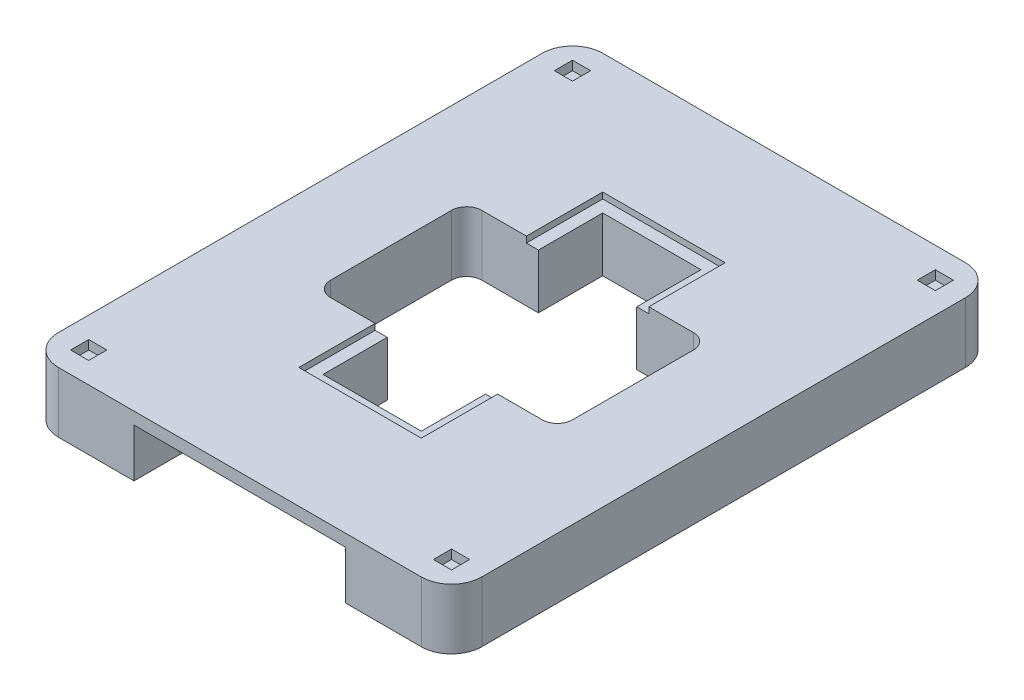
SolidWorks part; units mm, degrees
ref_plane "前视基准面" through (0, 0, 0) normal (0, 0, 1) x (1, 0, 0)
ref_plane "上视基准面" through (0, 0, 0) normal (0, 1, 0) x (1, 0, 0)
ref_plane "右视基准面" through (0, 0, 0) normal (1, 0, 0) x (0, 0, -1)
sketch "草图1" plane through (0, 0, 0) normal (0, 1, 0) x (1, 0, 0)
  line L1 (100, -100) -> (-100, -100)
  line L2 (100, -100) -> (100, 100)
  line L3 (100, 100) -> (-100, 100)
  line L4 (-100, -100) -> (-100, 100)
  line L5 (100, -100) -> (-100, 100) construction
  line L6 (100, 100) -> (-100, -100) construction
  point P1 (0, 0)
  dimension "D1" = 200
  dimension "D2" = 200
extrude "凸台-拉伸1" add sketch "草图1" along normal blind 20
sketch "草图2" plane through (0, 20, 0) normal (0, 1, 0) x (1, 0, 0)
  line L1 (70, -90) -> (-70, -90)
  line L2 (70, -90) -> (70, 90)
  line L3 (70, 90) -> (-70, 90)
  line L4 (-70, -90) -> (-70, 90)
  line L5 (70, -90) -> (-70, 90) construction
  line L6 (70, 90) -> (-70, -90) construction
  line L7 (100, -100) -> (-100, -100)
  line L8 (100, -100) -> (100, 100)
  line L9 (100, 100) -> (-100, 100)
  line L10 (-100, -100) -> (-100, 100)
  line L11 (100, -100) -> (-100, 100) construction
  line L12 (100, 100) -> (-100, -100) construction
  point P0 (0, 0)
  point P6 (0, 0)
  dimension "D1" = 140
  dimension "D2" = 180
extrude "切除-拉伸2" cut sketch "草图2" against normal through all
fillet "圆角1" radius 10 1 edges at (-70, 10, -90)
fillet "圆角2" radius 10 1 edges at (70, 10, -90)
fillet "圆角3" radius 10 1 edges at (70, 10, 90)
fillet "圆角4" radius 10 1 edges at (-70, 10, 90)
sketch "草图4" plane through (0, 0, 0) normal (0, -1, 0) x (1, 0, 0)
  line L5 (-60, 90) -> (60, 90) construction
  line L82 (-70, -80) -> (-70, 80) construction
  line L83 (-59.5, 84.9749) -> (-59.5, 86)
  line L95 (-59.5, 74) -> (-60.5, 74)
  line L97 (-59.5, 74) -> (-59.5, 75.0251)
  line L102 (-59.5, 86) -> (-60.5, 86)
  line L103 (-60.5, 74) -> (-60.5, 75.0251)
  line L108 (-66, 79.5) -> (-64.9749, 79.5)
  line L109 (-66, 79.5) -> (-66, 80.5)
  line L110 (-66, 80.5) -> (-64.9749, 80.5)
  line L111 (-54, 79.5) -> (-54, 80.5)
  line L115 (-60.5, 84.9749) -> (-60.5, 86)
  line L116 (-55.0251, 80.5) -> (-54, 80.5)
  line L120 (-55.0251, 79.5) -> (-54, 79.5)
  arc A5 (-60.5, 84.9749) -> (-64.9749, 80.5) centre (-60, 80) ccw
  arc A6 (-55.0251, 80.5) -> (-59.5, 84.9749) centre (-60, 80) ccw
  arc A7 (-59.5, 75.0251) -> (-55.0251, 79.5) centre (-60, 80) ccw
  arc A8 (-64.9749, 79.5) -> (-60.5, 75.0251) centre (-60, 80) ccw
  point P0 (0, 0)
  point P2 (-60, 80)
  dimension "D3" = 1
  dimension "D4" = 12
  dimension "D1" = 10
  dimension "D2" = 10
  dimension "D5" = 1
  dimension "D6" = 12
extrude "切除-拉伸4" cut sketch "草图4" against normal blind 5
mirror "镜向3" about plane through (0, 0, 0) normal (1, 0, 0) of "切除-拉伸4" second plane through (0, 0, 0) second plane normal (0, 0, 1)
sketch "草图5" plane through (0, 0, 0) normal (0, -1, 0) x (1, 0, 0)
  line L1 (60, -80) -> (-60, -80) construction
  line L2 (60, -80) -> (60, 80) construction
  line L3 (60, 80) -> (-60, 80) construction
  line L4 (-60, -80) -> (-60, 80) construction
  line L5 (60, -80) -> (-60, 80) construction
  line L6 (60, 80) -> (-60, -80) construction
  circle A0 centre (-60, 80) radius 5
  point P0 (0, 0)
  dimension "D3" = 10
  dimension "D1" = 120
  dimension "D2" = 160
extrude "切除-拉伸5" cut sketch "草图5" against normal blind 6.2
sketch "草图7" plane through (0, 0, 0) normal (0, -1, 0) x (1, 0, 0)
  line L0 (-60, 90) -> (60, 90) construction
  line L1 (35, 110) -> (-35, 110)
  line L2 (35, 110) -> (35, 75)
  line L3 (30, 70) -> (-30, 70)
  line L4 (-35, 110) -> (-35, 75)
  line L5 (35, 110) -> (-35, 70) construction
  line L6 (35, 70) -> (-35, 110) construction
  arc A0 (-30, 70) -> (-35, 75) centre (-30, 75) cw
  arc A1 (30, 70) -> (35, 75) centre (30, 75) ccw
  point P0 (0, 90)
  dimension "D3" = 5
  dimension "D4" = 5
  dimension "D1" = 70
  dimension "D2" = 40
extrude "切除-拉伸7" cut sketch "草图7" against normal blind 16
mirror "镜向6" about plane through (0, 0, 0) normal (0, 0, 1) of "切除-拉伸7"
sketch "草图8" plane through (0, 0, 0) normal (0, -1, 0) x (1, 0, 0)
  line L5 (40.5, -40.5) -> (-40.5, -40.5) construction
  line L6 (40.5, -40.5) -> (40.5, 40.5) construction
  line L7 (40.5, 40.5) -> (-40.5, 40.5) construction
  line L8 (-40.5, -40.5) -> (-40.5, 40.5) construction
  line L9 (40.5, -40.5) -> (-40.5, 40.5) construction
  line L10 (40.5, 40.5) -> (-40.5, -40.5) construction
  circle A4 centre (-40.5, 40.5) radius 4.1
  point P0 (0, 0)
  dimension "D1" = 81
  dimension "D2" = 81
extrude "切除-拉伸8" cut sketch "草图8" against normal blind 4
draft "拔模2" type of draft neutral plane draft angle 10 faces to draft 1 face at (-40.5, 4, 36.4) neutral plane through (-40.5, 4, 40.5) neutral plane normal (0, -1, 0) parameters "D1"=10
mirror "镜向10" about plane through (0, 0, 0) normal (1, 0, 0) of "拔模2", "切除-拉伸8"
mirror "镜向11" about plane through (0, 0, 0) normal (0, 0, 1) of "切除-拉伸8", "拔模2"
sketch "草图14" plane through (0, 20, 0) normal (0, 1, 0) x (1, 0, 0)
  line L1 (60, -80) -> (-60, -80) construction
  line L2 (60, -80) -> (60, 80) construction
  line L3 (60, 80) -> (-60, 80) construction
  line L4 (-60, -80) -> (-60, 80) construction
  line L5 (60, -80) -> (-60, 80) construction
  line L6 (60, 80) -> (-60, -80) construction
  line L7 (-57, 77) -> (-63, 77)
  line L8 (-57, 77) -> (-57, 83)
  line L9 (-57, 83) -> (-63, 83)
  line L10 (-63, 77) -> (-63, 83)
  line L11 (-57, 77) -> (-63, 83) construction
  line L12 (-57, 83) -> (-63, 77) construction
  point P0 (0, 0)
  dimension "D1" = 120
  dimension "D2" = 160
  dimension "D3" = 6
  dimension "D4" = 6
extrude "切除-拉伸9" cut sketch "草图14" against normal blind 3
mirror "镜向12" about plane through (0, 0, 0) normal (1, 0, 0) of "切除-拉伸9" second plane through (0, 0, 0) second plane normal (0, 0, 1)
sketch "草图16" plane through (0, 20, 0) normal (0, 1, 0) x (1, 0, 0)
  line L1 (20.25, -50.25) -> (-20.25, -50.25)
  line L2 (20.25, -50.25) -> (20.25, 50.25)
  line L3 (20.25, 50.25) -> (-20.25, 50.25)
  line L4 (-20.25, -50.25) -> (-20.25, 50.25)
  line L5 (20.25, -50.25) -> (-20.25, 50.25) construction
  line L6 (20.25, 50.25) -> (-20.25, -50.25) construction
  point P0 (0, 0)
  dimension "D1" = 40.5
  dimension "D2" = 100.5
extrude "切除-拉伸10" cut sketch "草图16" against normal blind 2
sketch "草图17" plane through (0, 18, 0) normal (0, 1, 0) x (1, 0, 0)
  line L1 (16.25, -46.25) -> (-16.25, -46.25)
  line L2 (16.25, -46.25) -> (16.25, 46.25)
  line L3 (16.25, 46.25) -> (-16.25, 46.25)
  line L4 (-16.25, -46.25) -> (-16.25, 46.25)
  line L5 (16.25, -46.25) -> (-16.25, 46.25) construction
  line L6 (16.25, 46.25) -> (-16.25, -46.25) construction
  point P0 (0, 0)
  dimension "D1" = 32.5
  dimension "D2" = 92.5
extrude "切除-拉伸11" cut sketch "草图17" against normal through all
sketch "草图18" plane through (0, 20, 0) normal (0, 1, 0) x (1, 0, 0)
  line L1 (35, -25) -> (-35, -25)
  line L2 (40, -20) -> (40, 20)
  line L3 (35, 25) -> (-35, 25)
  line L4 (-40, -20) -> (-40, 20)
  line L5 (40, -25) -> (-40, 25) construction
  line L6 (40, 25) -> (-40, -25) construction
  arc A0 (-40, 20) -> (-35, 25) centre (-35, 20) cw
  arc A1 (-40, -20) -> (-35, -25) centre (-35, -20) ccw
  arc A2 (40, -20) -> (35, -25) centre (35, -20) cw
  arc A3 (40, 20) -> (35, 25) centre (35, 20) ccw
  point P0 (0, 0)
  dimension "D3" = 5
  dimension "D4" = 5
  dimension "D1" = 80
  dimension "D2" = 50
extrude "切除-拉伸12" cut sketch "草图18" against normal through all
